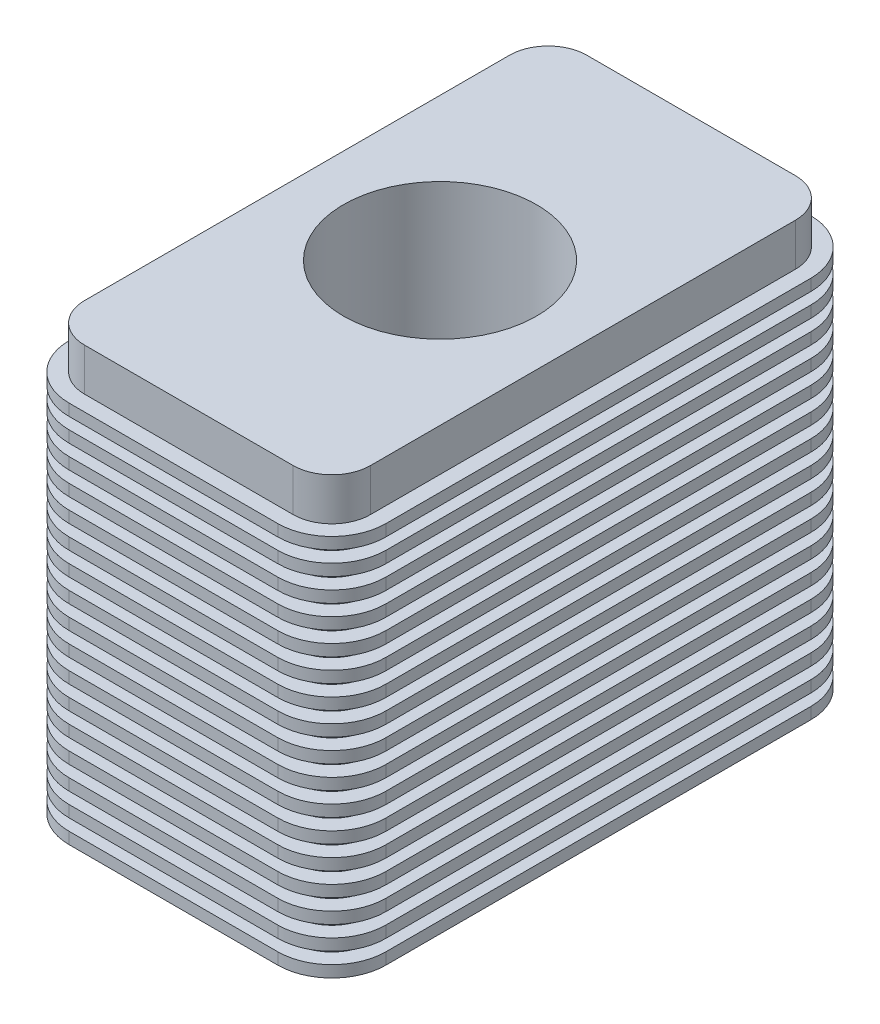
SolidWorks part; units mm, degrees
ref_plane "Front Plane" through (0, 0, 0) normal (0, 0, 1) x (1, 0, 0)
ref_plane "Top Plane" through (0, 0, 0) normal (0, 1, 0) x (1, 0, 0)
ref_plane "Right Plane" through (0, 0, 0) normal (1, 0, 0) x (0, 0, -1)
sketch "Sketch1" plane through (0, 0, 0) normal (0, 1, 0) x (1, 0, 0)
  line L0 (25, 0) -> (37, 0)
  line L1 (37, 0) -> (37, 55)
  line L2 (27, 65) -> (-27, 65)
  line L3 (0, 0) -> (0, 90.8775) construction
  line L4 (-25, 0) -> (-37, 0)
  line L5 (-37, 0) -> (-37, 55)
  arc A0 (25, 0) -> (-25, 0) centre (0, 0) ccw
  arc A1 (37, 55) -> (27, 65) centre (27, 55) ccw
  arc A2 (-37, 55) -> (-27, 65) centre (-27, 55) cw
  point P11 (0, 65)
  point P13 (37, 65)
  point P16 (-37, 65)
  dimension "D1" = 50
  dimension "D4" = 10
  dimension "D2" = 12
  dimension "D3" = 65
extrude "Boss-Extrude1" add sketch "Sketch1" along normal blind 110
sketch "Sketch3" plane through (0, 0, 0) normal (0, -1, 0) x (-1, 0, 0)
  line L0 (37, 0) -> (37, 55)
  line L6 (25, 0) -> (37, 0)
  line L7 (37, 0) -> (37, 55)
  line L8 (27, 65) -> (-27, 65)
  line L9 (-37, 55) -> (-37, 0)
  line L10 (-37, 0) -> (-25, 0)
  line L12 (37, 0) -> (37, 55)
  line L13 (27, 65) -> (-27, 65)
  line L14 (-37, 55) -> (-37, 0)
  line L16 (37, 0) -> (41, 0)
  line L17 (-37, 0) -> (-41, 0)
  line L21 (20.6155, -4) -> (41, -4)
  line L22 (41, -4) -> (41, 55)
  line L23 (27, 69) -> (-27, 69)
  line L24 (-41, 55) -> (-41, -4)
  line L25 (-41, -4) -> (-20.6155, -4)
  line L27 (41, 0) -> (41, 55)
  line L28 (27, 69) -> (-27, 69)
  line L29 (-41, 55) -> (-41, 0)
  arc A3 (25, 0) -> (-25, 0) centre (0, 0) ccw
  arc A4 (37, 55) -> (27, 65) centre (27, 55) ccw
  arc A5 (-27, 65) -> (-37, 55) centre (-27, 55) ccw
  arc A7 (37, 55) -> (27, 65) centre (27, 55) ccw
  arc A8 (-27, 65) -> (-37, 55) centre (-27, 55) ccw
  arc A12 (20.6155, -4) -> (-20.6155, -4) centre (0, 0) ccw
  arc A13 (41, 55) -> (27, 69) centre (27, 55) ccw
  arc A14 (-27, 69) -> (-41, 55) centre (-27, 55) ccw
  arc A16 (41, 55) -> (27, 69) centre (27, 55) ccw
  arc A17 (-27, 69) -> (-41, 55) centre (-27, 55) ccw
  line M20 (37, 0) -> (37, 55)
  arc M21 (37, 55) -> (27, 65) centre (27, 55) ccw
  line M22 (27, 65) -> (-27, 65)
  arc M23 (-27, 65) -> (-37, 55) centre (-27, 55) ccw
  line M24 (-37, 55) -> (-37, 0)
  dimension "D1" = 0
  dimension "D2" = 4
extrude "Boss-Extrude3" add sketch "Sketch3" against normal blind 3 separate body contours L28 A17 L29 L17 L16 L27 A16 M24 M23 M22 M21 M20
pattern_linear "LPattern1" count 17 spacing 6 along (0, 1, 0) of "Boss-Extrude3"
mirror "Mirror1" about plane through (0, 0, 0) normal (0, 0, 1) of "LPattern1", "Boss-Extrude1", "Boss-Extrude3"
